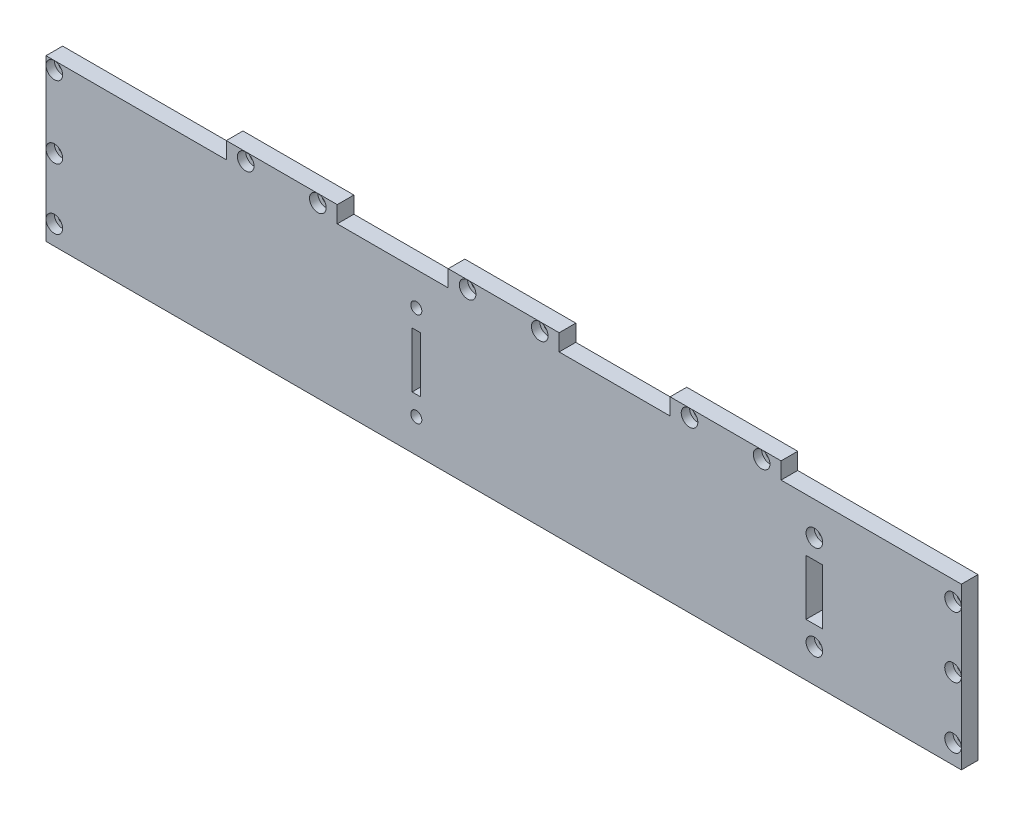
SolidWorks part; units mm, degrees
ref_plane "Plan de face" through (0, 0, 0) normal (0, 0, 1) x (1, 0, 0)
ref_plane "Plan de dessus" through (0, 0, 0) normal (0, 1, 0) x (1, 0, 0)
ref_plane "Plan de droite" through (0, 0, 0) normal (1, 0, 0) x (0, 0, -1)
sketch "Esquisse1" plane through (0, 0, 0) normal (0, 0, 1) x (1, 0, 0)
  line L1 (0, 0) -> (-330, 0)
  line L2 (0, 0) -> (0, 64)
  line L3 (0, 64) -> (-330, 64)
  line L4 (-330, 0) -> (-330, 64)
  dimension "D1" = 64
  dimension "D2" = 330
extrude "Boss.-Extru.1" add sketch "Esquisse1" along normal blind 6
sketch "Esquisse2" plane through (0, 0, 6) normal (0, 0, 1) x (1, 0, 0)
  line L0 (0, 64) -> (-330, 64) construction
  line L1 (-330, 64) -> (-265, 64)
  line L2 (-330, 64) -> (-330, 58)
  line L3 (-330, 58) -> (-265, 58)
  line L4 (-265, 64) -> (-265, 58)
  line L5 (-225, 64) -> (-185, 64)
  line L6 (-225, 64) -> (-225, 58)
  line L7 (-225, 58) -> (-185, 58)
  line L8 (-185, 64) -> (-185, 58)
  line L10 (-145, 64) -> (-105, 64)
  line L11 (-145, 64) -> (-145, 58)
  line L12 (-145, 58) -> (-105, 58)
  line L13 (-105, 64) -> (-105, 58)
  line L14 (0, 64) -> (-65, 64)
  line L15 (0, 64) -> (0, 58)
  line L16 (0, 58) -> (-65, 58)
  line L17 (-65, 64) -> (-65, 58)
  dimension "D1" = 6
  dimension "D2" = 6
  dimension "D3" = 6
  dimension "D4" = 6
  dimension "D5" = 65
  dimension "D6" = 40
  dimension "D7" = 40
  dimension "D8" = 65
  dimension "D9" = 40
  dimension "D10" = 40
extrude "Enlèv. mat.-Extru.1" cut sketch "Esquisse2" against normal through all
sketch "Esquisse3" plane through (0, 0, 6) normal (0, 0, 1) x (1, 0, 0)
  line L0 (-330, 58) -> (-330, 0) construction
  line L1 (-198, 39) -> (-195, 39)
  line L2 (-198, 39) -> (-198, 19)
  line L3 (-198, 19) -> (-195, 19)
  line L4 (-195, 39) -> (-195, 19)
  line L5 (-56, 39) -> (-50, 39)
  line L6 (-56, 39) -> (-56, 19)
  line L7 (-56, 19) -> (-50, 19)
  line L8 (-50, 39) -> (-50, 19)
  line L9 (-225, 58) -> (-185, 58) construction
  line L11 (0, 0) -> (0, 58) construction
  line L12 (-65, 58) -> (0, 58) construction
  dimension "D1" = 3
  dimension "D2" = 20
  dimension "D3" = 6
  dimension "D4" = 20
  dimension "D5" = 132
  dimension "D6" = 19
  dimension "D7" = 50
  dimension "D8" = 19
extrude "Enlèv. mat.-Extru.2" cut sketch "Esquisse3" against normal through all
sketch "Esquisse4" plane through (0, 0, 6) normal (0, 0, 1) x (1, 0, 0)
  line L0 (-330, 58) -> (-265, 58) construction
  line L1 (-330, 58) -> (-330, 0) construction
  line L2 (-330, 0) -> (0, 0) construction
  line L3 (-330, 58) -> (-330, 0) construction
  line L4 (-265, 58) -> (-265, 64) construction
  line L5 (-225, 64) -> (-265, 64) construction
  line L6 (-225, 64) -> (-225, 58) construction
  line L7 (-185, 58) -> (-185, 64) construction
  line L8 (-145, 64) -> (-185, 64) construction
  line L9 (-145, 64) -> (-145, 58) construction
  line L10 (-105, 58) -> (-105, 64) construction
  line L11 (-65, 64) -> (-105, 64) construction
  line L12 (-65, 64) -> (-65, 58) construction
  line L13 (-65, 58) -> (0, 58) construction
  line L14 (0, 0) -> (0, 58) construction
  line L15 (-50, 39) -> (-56, 39) construction
  line L16 (-50, 19) -> (-50, 39) construction
  line L17 (-56, 39) -> (-56, 19) construction
  line L18 (-56, 19) -> (-50, 19) construction
  line L19 (-198, 39) -> (-198, 19) construction
  line L21 (-198, 19) -> (-195, 19) construction
  line L22 (-195, 39) -> (-198, 39) construction
  line L23 (-195, 19) -> (-195, 39) construction
  circle A0 centre (-327, 55) radius 1.5
  circle A1 centre (-327, 29) radius 1.5
  circle A2 centre (-327, 7) radius 1.5
  circle A3 centre (-258, 61) radius 1.5
  circle A4 centre (-232, 61) radius 1.5
  circle A5 centre (-178, 61) radius 1.5
  circle A6 centre (-152, 61) radius 1.5
  circle A7 centre (-98, 61) radius 1.5
  circle A8 centre (-72, 61) radius 1.5
  circle A9 centre (-53, 46) radius 1.5
  circle A10 centre (-53, 12) radius 1.5
  circle A11 centre (-196.5, 46) radius 1.005
  circle A12 centre (-196.5, 12) radius 1.005
  circle A13 centre (-3, 51) radius 1.5
  circle A14 centre (-3, 29) radius 1.5
  circle A15 centre (-3, 7) radius 1.5
  point P51 (-187.9456, 63.012)
  point P52 (-145, 61)
  dimension "D1" = 3
  dimension "D2" = 3
  dimension "D3" = 3
  dimension "D4" = 3
  dimension "D5" = 7
  dimension "D6" = 3
  dimension "D7" = 3
  dimension "D8" = 3
  dimension "D9" = 29
  dimension "D10" = 3
  dimension "D11" = 7
  dimension "D12" = 3
  dimension "D13" = 3
  dimension "D14" = 3
  dimension "D15" = 7
  dimension "D16" = 3
  dimension "D17" = 7
  dimension "D18" = 3
  dimension "D19" = 3
  dimension "D20" = 3
  dimension "D21" = 7
  dimension "D22" = 3
  dimension "D23" = 3
  dimension "D24" = 7
  dimension "D25" = 3
  dimension "D26" = 7
  dimension "D27" = 3
  dimension "D28" = 3
  dimension "D29" = 7
  dimension "D30" = 3
  dimension "D31" = 3
  dimension "D32" = 3
  dimension "D33" = 3
  dimension "D34" = 7
  dimension "D35" = 3
  dimension "D36" = 29
  dimension "D37" = 3
  dimension "D38" = 7
  dimension "D39" = 3
  dimension "D40" = 3
  dimension "D41" = 3
  dimension "D42" = 7
  dimension "D43" = 2.01
  dimension "D44" = 1.5
  dimension "D45" = 7
  dimension "D46" = 2.01
  dimension "D47" = 7
  dimension "D48" = 1.5
extrude "Enlèv. mat.-Extru.3" cut sketch "Esquisse4" against normal through all
sketch "Esquisse5" plane through (0, 0, 6) normal (0, 0, 1) x (1, 0, 0)
  circle A0 centre (-327, 7) radius 2.995
  circle A1 centre (-327, 29) radius 2.995
  circle A2 centre (-327, 55) radius 2.995
  circle A3 centre (-258, 61) radius 2.995
  circle A4 centre (-232, 61) radius 2.995
  circle A5 centre (-196.5, 46) radius 2
  circle A6 centre (-178, 61) radius 2.995
  circle A7 centre (-152, 61) radius 2.995
  circle A8 centre (-98, 61) radius 2.995
  circle A9 centre (-72, 61) radius 2.995
  circle A10 centre (-53, 46) radius 2.995
  circle A11 centre (-53, 12) radius 2.995
  circle A12 centre (-3, 7) radius 2.995
  circle A13 centre (-3, 29) radius 2.995
  circle A14 centre (-3, 51) radius 2.995
  circle A15 centre (-196.5, 12) radius 2
  dimension "D1" = 5.99
  dimension "D2" = 5.99
  dimension "D3" = 5.99
  dimension "D4" = 5.99
  dimension "D5" = 5.99
  dimension "D6" = 5.99
  dimension "D7" = 5.99
  dimension "D8" = 5.99
  dimension "D9" = 5.99
  dimension "D10" = 4
  dimension "D11" = 5.99
  dimension "D12" = 5.99
  dimension "D13" = 5.99
  dimension "D14" = 5.99
  dimension "D15" = 5.99
  dimension "D16" = 4
extrude "Enlèv. mat.-Extru.4" cut sketch "Esquisse5" against normal blind 3
